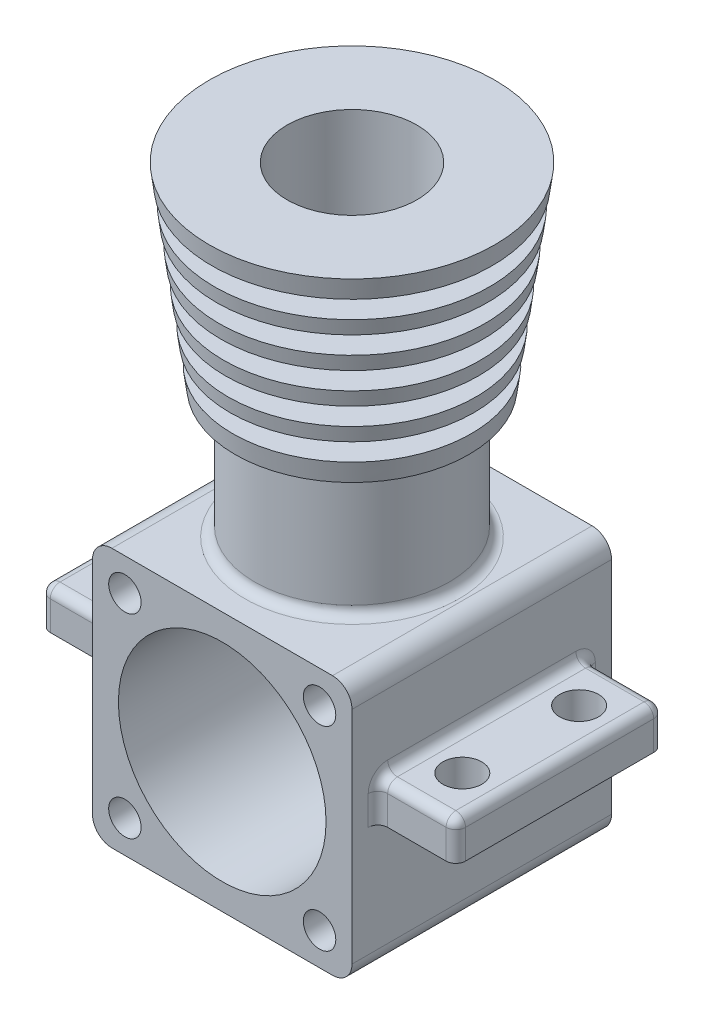
SolidWorks part; units mm, degrees
ref_plane "Front Plane" through (0, 0, 0) normal (0, 0, 1) x (1, 0, 0)
ref_plane "Top Plane" through (0, 0, 0) normal (0, 1, 0) x (1, 0, 0)
ref_plane "Right Plane" through (0, 0, 0) normal (1, 0, 0) x (0, 0, -1)
sketch "Sketch1" plane through (0, 0, 0) normal (0, 0, 1) x (1, 0, 0)
  line L1 (-20, 20) -> (20, 20)
  line L2 (-20, 20) -> (-20, -20)
  line L3 (-20, -20) -> (20, -20)
  line L4 (20, 20) -> (20, -20)
  line L5 (-20, 20) -> (20, -20) construction
  line L6 (-20, -20) -> (20, 20) construction
  line L7 (-15, 15) -> (15, 15) construction
  line L8 (-15, 15) -> (-15, -15) construction
  line L9 (-15, -15) -> (15, -15) construction
  line L10 (15, 15) -> (15, -15) construction
  line L11 (-15, 15) -> (15, -15) construction
  line L12 (-15, -15) -> (15, 15) construction
  circle A0 centre (-15, 15) radius 2.5
  circle A1 centre (15, 15) radius 2.5
  circle A2 centre (15, -15) radius 2.5
  circle A3 centre (-15, -15) radius 2.5
  circle A4 centre (0, 0) radius 16
  point P0 (0, 0)
  point P6 (0, 0)
  dimension "D1" = 32
  dimension "D5" = 5
  dimension "D2" = 40
  dimension "D3" = 40
  dimension "D4" = 5
extrude "Boss-Extrude2" add sketch "Sketch1" along normal mid plane 40
fillet "Fillet2" radius 3 4 edges at (-20, -20, 0) (20, -20, 0) (20, 20, 0) (-20, 20, 0)
sketch "Sketch2" plane through (0, 0, 0) normal (0, 0, 1) x (1, 0, 0)
  line L0 (0, 20) -> (0, 70)
  line L1 (17, 20) -> (-17, 20) construction
  line L2 (0, -55) -> (0, 55) construction
  line L3 (0, 70) -> (-22, 70)
  line L4 (-22, 70) -> (-18, 40)
  line L5 (-18, 40) -> (-15, 40)
  line L6 (-15, 40) -> (-15, 20)
  line L7 (-15, 20) -> (0, 20)
  dimension "D1" = 22
  dimension "D2" = 50
  dimension "D3" = 20
  dimension "D4" = 15
  dimension "D5" = 18
revolve "Revolve1" add sketch "Sketch2" angle 360 about L0
sketch "Sketch3" plane through (0, 0, 0) normal (0, 0, 1) x (1, 0, 0)
  line L0 (-18, 40) -> (18, 40) construction
  line L1 (-30, 46) -> (-12, 46)
  line L2 (-30, 46) -> (-30, 43)
  line L3 (-30, 43) -> (-12, 43)
  line L4 (-12, 46) -> (-12, 43)
  line L5 (-30, 46) -> (-12, 43) construction
  line L6 (-30, 43) -> (-12, 46) construction
  line L7 (0, -55) -> (0, 55) construction
  line L8 (0, 34.2049) -> (0, 77.0734) construction
  point P0 (-21, 44.5)
  dimension "D1" = 3
  dimension "D2" = 3
  dimension "D3" = 12
  dimension "D4" = 30
revolve "Cut-Revolve1" cut sketch "Sketch3" angle 360 about L8
pattern_linear "LPattern1" count 5 spacing 5.25 along (0, 1, 0) of "Cut-Revolve1"
sketch "Sketch6" plane through (0, 70, 0) normal (0, 1, 0) x (1, 0, 0)
  circle A0 centre (0, 0) radius 10
  dimension "D1" = 20
extrude "Cut-Extrude2" cut sketch "Sketch6" against normal up to surface (70 mm away) contours A0 up to plane "Top Plane"
sketch "Sketch7" plane through (0, 0, 0) normal (0, 1, 0) x (1, 0, 0)
  line L0 (-20, -16) -> (-32, -16)
  line L1 (-20, -20) -> (-20, 20) construction
  line L2 (-32, -16) -> (-32, 16)
  line L3 (-32, 16) -> (-20, 16)
  line L4 (-20, 16) -> (-20, -16)
  line L5 (-55, 0) -> (55, 0) construction
  line L6 (28.6364, 0) -> (-37.135, 0) construction
  line L7 (0, -55) -> (0, 55) construction
  circle A0 centre (-26, 9) radius 3
  circle A1 centre (-26, -9) radius 3
  dimension "D3" = 18
  dimension "D4" = 6
  dimension "D1" = 12
  dimension "D2" = 32
  dimension "D5" = 26
extrude "Boss-Extrude4" add sketch "Sketch7" along normal blind 6
mirror "Mirror1" about plane through (0, 0, 0) normal (1, 0, 0) of "Boss-Extrude4"
fillet "Fillet3" radius 1.5 17 edges at (-26, 6, -16) (-32, 3, -16) (32, 3, 16) (26, 6, -16) (20, 6, 0) (20, 3, -16) (32, 3, -16) (32, 6, 0) (26, 6, 16) (20, 3, 16) (-32, 6, 0) (-20, 3, -16) (-32, 3, 16) (-20, 3, 16) (-26, 6, 16) (-20, 6, 0) (0, 20, -15)
